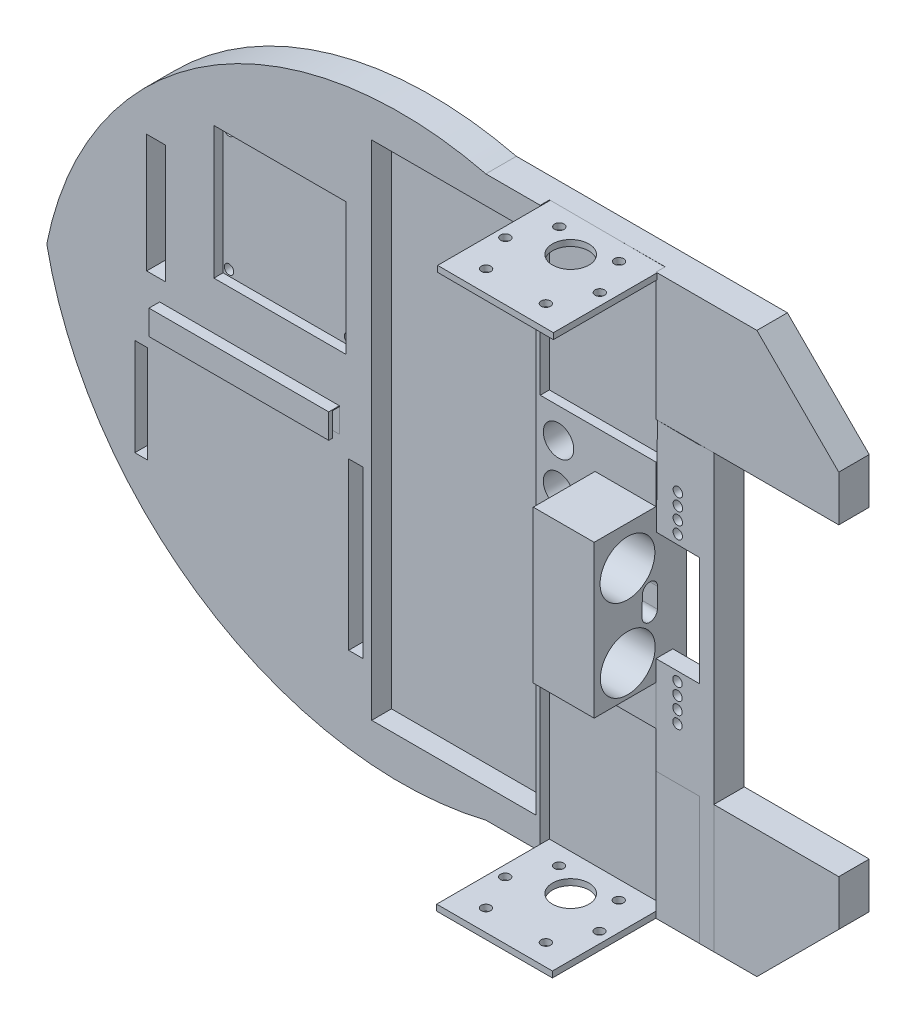
SolidWorks part; units mm, degrees
ref_plane "Front Plane" through (0, 0, 0) normal (0, 0, 1) x (1, 0, 0)
ref_plane "Top Plane" through (0, 0, 0) normal (0, 1, 0) x (1, 0, 0)
ref_plane "Right Plane" through (0, 0, 0) normal (1, 0, 0) x (0, 0, -1)
sketch "Sketch1" plane through (0, 0, 0) normal (0, 0, 1) x (1, 0, 0)
  line L1 (0, 0) -> (0, -50)
  line L2 (0, 50) -> (60, 50)
  line L3 (0, -50) -> (60, -50)
  line L4 (60, 50) -> (60, 65)
  line L5 (60, -50) -> (60, -65)
  line L6 (60, 65) -> (33.1299, 91.8701)
  line L7 (33.1299, 91.8701) -> (-55.8501, 91.8701)
  line L8 (60, -65) -> (33.1299, -91.8701)
  line L9 (33.1299, -91.8701) -> (-55.8501, -91.8701)
  line L10 (-55.8501, 91.8701) -> (-55.8501, 169.9436) construction
  line L11 (-55.8501, 169.9436) -> (-55.8501, -262.005) construction
  line L22 (0, 50) -> (0, 0)
  line L24 (-83.882, 95.237) -> (-230.9548, 95.237) construction
  line L25 (-83.882, 23.2048) -> (-83.882, 138.7176) construction
  line L26 (-83.882, -23.1381) -> (-83.882, -112.3942) construction
  line L27 (-83.882, -95.2351) -> (-171.3154, -95.2351) construction
  arc A7 (-200, -0.1322) -> (-55.8501, 91.8701) centre (-83.882, -23.1381) cw
  arc A8 (-55.8501, -91.8701) -> (-200, -0.1322) centre (-83.882, 23.2048) cw
  dimension "D11" = 199.5908
  dimension "D12" = 200
  dimension "D10" = 183.7401
  dimension "D1" = 50
  dimension "D2" = 50
  dimension "D3" = 60
  dimension "D4" = 15
  dimension "D5" = 15
  dimension "D6" = 135
  dimension "D7" = 38
  dimension "D8" = 38
  dimension "D9" = 135
  dimension "D15" = 88.98
  dimension "D16" = 88.98
extrude "Boss-Extrude1" add sketch "Sketch1" along normal blind 10 and the other way blind 0.01
sketch "Sketch3" plane through (0, 0, 10) normal (0, 0, 1) x (1, 0, 0)
  line L0 (33.1299, 91.8701) -> (-55.8501, 91.8701) construction
  line L1 (-38, 91.8701) -> (0, 91.8701)
  line L2 (-38, 91.8701) -> (-38, 37.8701)
  line L3 (-38, 37.8701) -> (0, 37.8701)
  line L4 (0, 91.8701) -> (0, 37.8701)
  dimension "D1" = 54
extrude "Cut-Extrude1" cut sketch "Sketch3" against normal blind 3 contours L2 L1 L4 L3
sketch "Sketch5" plane through (0, 0, 10) normal (0, 0, 1) x (1, 0, 0)
  line L0 (-55.8501, -91.8701) -> (33.1299, -91.8701) construction
  line L1 (-38, -37.8701) -> (0, -37.8701)
  line L2 (-38, -37.8701) -> (-38, -91.8701)
  line L3 (-38, -91.8701) -> (0, -91.8701)
  line L4 (0, -37.8701) -> (0, -91.8701)
  dimension "D1" = 54
extrude "Cut-Extrude3" cut sketch "Sketch5" against normal blind 3
sketch "Sketch7" plane through (0, 0, 10) normal (0, 0, 1) x (1, 0, 0)
  line L9 (-93.3252, 82.7857) -> (-39.3252, 82.7857)
  line L10 (-93.3252, 82.7857) -> (-93.3252, -82.2143)
  line L11 (-93.3252, -82.2143) -> (-39.3252, -82.2143)
  line L12 (-39.3252, 82.7857) -> (-39.3252, -82.2143)
  dimension "D1" = 54
  dimension "D2" = 165
extrude "Cut-Extrude4" cut sketch "Sketch7" against normal blind 6.5
sketch "Sketch8" plane through (0, 0, 10) normal (0, 0, 1) x (1, 0, 0)
  line L1 (-162.9927, 67.8133) -> (-84.7927, 67.8133)
  line L2 (-162.9927, 67.8133) -> (-162.9927, 10.3133)
  line L3 (-162.9927, 10.3133) -> (-84.7927, 10.3133)
  line L4 (-84.7927, 67.8133) -> (-84.7927, 10.3133)
  dimension "D1" = 78.2
  dimension "D2" = 57.5
extrude "Cut-Extrude5" [suppressed] cut sketch "Sketch8" against normal blind 3
sketch "Sketch9" plane through (0, 0, 10) normal (0, 0, 1) x (1, 0, 0)
  line L1 (-195, 36) -> (-176, 36)
  line L2 (-195, 36) -> (-195, 20)
  line L3 (-195, 20) -> (-176, 20)
  line L4 (-176, 36) -> (-176, 20)
  line L5 (-95.7317, 17.4542) -> (-82.493, 17.4542)
  line L6 (-95.7317, 17.4542) -> (-95.7317, 7.0108)
  line L7 (-95.7317, 7.0108) -> (-82.493, 7.0108)
  line L8 (-82.493, 17.4542) -> (-82.493, 7.0108)
  line L9 (-131.8867, -50.9252) -> (-116.9909, -50.9252)
  line L10 (-131.8867, -50.9252) -> (-131.8867, -65.1638)
  line L11 (-131.8867, -65.1638) -> (-116.9909, -65.1638)
  line L12 (-116.9909, -50.9252) -> (-116.9909, -65.1638)
extrude "Boss-Extrude2" [suppressed] add sketch "Sketch9" along normal blind 20.3
sketch "Sketch15" plane through (0, 0, 10) normal (0, 0, 1) x (1, 0, 0)
  line L0 (0, -37.8701) -> (0, 37.8701) construction
  line L1 (-20, 25.2016) -> (0, 25.2016)
  line L2 (-20, 25.2016) -> (-20, -24.7984)
  line L3 (-20, -24.7984) -> (0, -24.7984)
  line L4 (0, 25.2016) -> (0, -24.7984)
  dimension "D1" = 50
  dimension "D2" = 20
extrude "Boss-Extrude3" add sketch "Sketch15" along normal blind 20.3
sketch "Sketch16" plane through (0, 0, 10) normal (0, 0, 1) x (1, 0, 0)
  line L1 (-232.4208, 4) -> (-224.8235, 4)
  line L2 (-232.4208, 4) -> (-232.4208, -4)
  line L3 (-232.4208, -4) -> (-224.8235, -4)
  line L4 (-224.8235, 4) -> (-224.8235, -4)
  line L9 (-134.6881, 94.0493) -> (-144.6881, 94.0493)
  line L10 (-134.6881, 94.0493) -> (-134.6881, 84.6493)
  line L11 (-134.6881, 84.6493) -> (-144.6881, 84.6493)
  line L12 (-144.6881, 94.0493) -> (-144.6881, 84.6493)
  line L13 (-65.6779, 70.3488) -> (-74.3779, 70.3488)
  line L14 (-65.6779, 70.3488) -> (-65.6779, 61.8488)
  line L15 (-65.6779, 61.8488) -> (-74.3779, 61.8488)
  line L16 (-74.3779, 70.3488) -> (-74.3779, 61.8488)
  line L17 (-65.9779, -61.6233) -> (-75.3779, -61.6233)
  line L18 (-65.9779, -61.6233) -> (-65.9779, -70.9233)
  line L19 (-65.9779, -70.9233) -> (-75.3779, -70.9233)
  line L20 (-75.3779, -61.6233) -> (-75.3779, -70.9233)
  line L21 (-134.6881, -83.6815) -> (-144.6881, -83.6815)
  line L22 (-134.6881, -83.6815) -> (-134.6881, -92.9815)
  line L23 (-134.6881, -92.9815) -> (-144.6881, -92.9815)
  line L24 (-144.6881, -83.6815) -> (-144.6881, -92.9815)
extrude "Boss-Extrude4" [suppressed] add sketch "Sketch16" along normal blind 30
sketch "Sketch17" plane through (0, 0, 0) normal (0, 0, 1) x (1, 0, 0)
  circle A1 centre (-228.4208, 0) radius 2.55
  circle A2 centre (-139.6881, 89.6493) radius 3.5
  circle A3 centre (-69.8779, 66.3488) radius 3.5
  circle A4 centre (-69.8779, -66.6233) radius 3.5
  circle A5 centre (-139.6881, -88.6815) radius 3.5
extrude "Cut-Extrude17" [suppressed] cut sketch "Sketch17" along normal through all
sketch "Sketch18" plane through (0, 0, 10) normal (0, 0, 1) x (1, 0, 0)
  line L1 (-145.1245, 61) -> (-101.7245, 61)
  line L2 (-145.1245, 61) -> (-145.1245, 17.6)
  line L3 (-145.1245, 17.6) -> (-101.7245, 17.6)
  line L4 (-101.7245, 61) -> (-101.7245, 17.6)
  dimension "D1" = 43.4
  dimension "43.4" = 43.4
extrude "Cut-Extrude18" cut sketch "Sketch18" against normal blind 3
sketch "Sketch20" plane through (0, 0, 0) normal (0, 0, 1) x (1, 0, 0)
  circle A0 centre (-185.9471, 27.1121) radius 5
  circle A1 centre (-124.7094, -57.6129) radius 5
  circle A2 centre (-88.8879, 12.7504) radius 4
extrude "Cut-Extrude20" [suppressed] cut sketch "Sketch20" along normal through all
sketch "Sketch21" plane through (0, 0, 0) normal (1, 0, 0) x (0, 0, -1)
  line L0 (-3.8276, 29.0855) -> (-3.8276, -37.1575) construction
  line L1 (-6.4886, 28.3852) -> (-6.4886, -37.2976) construction
  line L2 (-5.0881, 28.1051) -> (-5.0881, -37.5777) construction
  line L3 (-11.99, 2.3019) -> (-12.0559, -4.1532) construction
  line L4 (-9.4916, 2.2764) -> (-9.5574, -4.1787)
  line L5 (-14.4885, 2.3274) -> (-14.5544, -4.1277)
  circle A0 centre (-19.3619, 12.3718) radius 9
  circle A1 centre (-19.2654, -14.6282) radius 9
  arc A2 (-9.4916, 2.2764) -> (-14.4885, 2.3274) centre (-11.99, 2.3019) ccw
  arc A3 (-14.5544, -4.1277) -> (-9.5574, -4.1787) centre (-12.0559, -4.1532) ccw
  point P12 (-12.023, -0.9256)
  dimension "D1" = 18
  dimension "D2" = 18
  dimension "D3" = 27
extrude "Cut-Extrude21" cut sketch "Sketch21" against normal up to surface (20 mm away) up to face at (-20, 0.2016, 20.15)
sketch "Sketch22" plane through (0, 0, 7) normal (0, 0, 1) x (1, 0, 0)
  circle A0 centre (-143.1686, 58.9795) radius 1.55
  circle A1 centre (-103.7686, 58.9795) radius 1.55
  circle A2 centre (-103.7686, 19.5795) radius 1.55
  circle A3 centre (-143.1686, 19.5795) radius 1.55
  dimension "D1" = 2
  dimension "D2" = 2
extrude "Cut-Extrude23" cut sketch "Sketch22" against normal through all
sketch "Sketch25" plane through (0, 0, 10) normal (0, 0, 1) x (1, 0, 0)
  line L5 (-162.9326, 1.9159) -> (-103.9326, 1.9159)
  line L6 (-162.9326, 1.9159) -> (-162.9326, -6.1841)
  line L7 (-162.9326, -6.1841) -> (-103.9326, -6.1841)
  line L8 (-103.9326, 1.9159) -> (-103.9326, -6.1841)
  dimension "D1" = 8.1
  dimension "D2" = 59
extrude "Boss-Extrude5" add sketch "Sketch25" along normal blind 3.5
sketch "Sketch26" plane through (0, -6.1841, 0) normal (0, -1, 0) x (1, 0, 0)
  line L0 (-172.679, 10.0037) -> (-152.674, 9.9893) construction
  line L1 (-152.674, 9.9893) -> (-152.6595, 14.6073) construction
extrude "Cut-Extrude24" [suppressed] cut sketch "Sketch26" against normal up to surface (58.5 mm away)
sketch "Sketch28" plane through (0, -91.8701, 0) normal (0, -1, 0) x (1, 0, 0)
  line L1 (14.2266, 10.0076) -> (18.9795, 10.0076)
  line L2 (14.2266, 10.0076) -> (14.2266, 0.0598)
  line L3 (14.2266, 0.0598) -> (18.9795, 0.0598)
  line L4 (18.9795, 10.0076) -> (18.9795, 0.0598)
extrude "Boss-Extrude6" add sketch "Sketch28" against normal up to surface (141.8701 mm away) up to face at (24, 50, 5.396)
sketch "Sketch34" plane through (0, 0, 10) normal (0, 0, 1) x (1, 0, 0)
  line L0 (0, 0) -> (85.4359, -0.2266) construction
  line L1 (53.8089, -34.3247) -> (61.9289, -40.2214)
  line L2 (53.8089, -34.3247) -> (57.1772, -29.6864)
  line L3 (61.9289, -40.2214) -> (65.2973, -35.5831)
  line L4 (57.1772, -29.6864) -> (65.2973, -35.5831)
  line L5 (62.1414, 39.8924) -> (65.4851, 35.2362)
  line L6 (57.3338, 29.3826) -> (65.4851, 35.2362)
  line L7 (53.9902, 34.0388) -> (57.3338, 29.3826)
  line L8 (53.9902, 34.0388) -> (62.1414, 39.8924)
extrude "Cut-Extrude27" [suppressed] cut sketch "Sketch34" against normal through all
sketch "Sketch36" plane through (0, 0, 7) normal (0, 0, 1) x (1, 0, 0)
  line L0 (0, 0) -> (106.9048, -0.1896) construction
  line L1 (0.3256, 91.8145) -> (0.3185, 89.8146)
  line L2 (0, -91.8151) -> (-38, -91.8151)
  line L3 (0, -91.8151) -> (0, -89.8151)
  line L4 (0, -89.8151) -> (-38, -89.8151)
  line L5 (-38, -91.8151) -> (-38, -89.8151)
  line L6 (-37.6741, 91.9493) -> (-37.6812, 89.9493)
  line L7 (0.3185, 89.8146) -> (-37.6812, 89.9493)
  line L8 (0.3256, 91.8145) -> (-37.6741, 91.9493)
  dimension "D1" = 2
extrude "Boss-Extrude7" add sketch "Sketch36" along normal blind 37
sketch "Sketch39" plane through (0, -91.8151, 0) normal (0, -1, 0) x (1, 0, 0)
  line L1 (-46.4365, 25) -> (22.9075, 25) construction
  line L4 (31.9978, 332) -> (-461.8231, 332) construction
  circle A1 centre (-19, 19) radius 6
  circle A2 centre (-34.4996, 25.0106) radius 1.55
  circle A3 centre (-3.5639, 24.9888) radius 1.55
  circle A4 centre (-28.8192, 37.0106) radius 1.55
  circle A5 centre (-9.1774, 36.9888) radius 1.55
  circle A6 centre (-28.82, 13.0106) radius 1.55
  circle A7 centre (-9.2305, 12.9888) radius 1.55
  point P18 (6.9989, 178.85)
  dimension "D1" = 12
  dimension "D5" = 12
  dimension "D6" = 12
  dimension "D7" = 12
  dimension "D8" = 12
  dimension "D2" = 19
extrude "Cut-Extrude28" cut sketch "Sketch39" against normal up to surface (2 mm away) up to face at (-19, -89.8151, 20.3333)
sketch "Sketch42" plane through (0.3256, 91.8145, 0) normal (0.0035, 1, 0) x (1, -0.0035, 0)
  circle A7 centre (-19.3258, -19) radius 6
  circle A9 centre (-29.0701, -13) radius 1.55
  circle A10 centre (-3.7784, -25) radius 1.55
  circle A11 centre (-9.4641, -13) radius 1.55
  circle A12 centre (-34.7723, -25) radius 1.55
  circle A13 centre (-29.0965, -37) radius 1.55
  circle A14 centre (-9.4734, -37) radius 1.55
  dimension "D1" = 12
  dimension "D5" = 6
  dimension "D6" = 6
  dimension "D7" = 6
  dimension "D8" = 6
  dimension "D9" = 18
  dimension "D10" = 18
  dimension "D2" = 19
extrude "Cut-Extrude29" cut sketch "Sketch42" against normal up to surface (2 mm away) up to face at (-12.4542, 89.8599, 20.3333)
sketch "Sketch44" plane through (-162.9326, 0, 0) normal (-1, 0, 0) x (0, 0, 1)
  line L1 (12.2622, 1.6288) -> (10.0122, 1.6288)
  line L2 (12.2622, 1.6288) -> (12.2622, -6.1912)
  line L3 (12.2622, -6.1912) -> (10.0122, -6.1912)
  line L4 (10.0122, 1.6288) -> (10.0122, -6.1912)
  dimension "D1" = 2.25
  dimension "D2" = 7.82
extrude "Cut-Extrude30" cut sketch "Sketch44" against normal up to surface (59 mm away) up to face at (-103.9326, -2.1341, 11.75)
sketch "Sketch45" plane through (0, 0, -0.01) normal (0, 0, -1) x (-1, 0, 0)
  line L0 (0, 0) -> (-86.1371, -0.4083) construction
  line L13 (-0.1707, 17.9992) -> (-0.474, 49.9978)
  line L14 (-16.5, -18) -> (0, -18)
  line L15 (-16.5, -18) -> (-16.5, -50)
  line L16 (-16.5, -50) -> (0, -50)
  line L17 (0, -18) -> (0, -50)
  line L18 (-16.9733, 49.8413) -> (-0.474, 49.9978)
  line L19 (-16.6699, 17.8428) -> (-16.9733, 49.8413)
  line L20 (-16.6699, 17.8428) -> (-0.1707, 17.9992)
extrude "Boss-Extrude8" add sketch "Sketch45" against normal up to surface (10.0176 mm away) up to face at (16.6031, -20.935, 10.0076)
sketch "Sketch30" plane through (0, 0, -0.01) normal (0, 0, -1) x (-1, 0, 0)
  line L0 (0.5881, -0.0011) -> (-26.6848, -0.0585) construction
  line L1 (0, -41.01) -> (-14.12, -41.01)
  line L2 (0, -41.01) -> (0, -16.01)
  line L3 (0, -16.01) -> (-14.12, -16.01)
  line L4 (-14.12, -41.01) -> (-14.12, -16.01)
  line L5 (-14.2924, 40.9456) -> (-14.1872, 15.9458)
  line L6 (-0.0674, 16.0052) -> (-14.1872, 15.9458)
  line L7 (-0.1725, 41.005) -> (-0.0674, 16.0052)
  line L8 (-0.1725, 41.005) -> (-14.2924, 40.9456)
  dimension "D1" = 25
  dimension "D2" = 14.12
extrude "Cut-Extrude25" cut sketch "Sketch30" against normal blind 4.5
sketch "Sketch33" plane through (0, 0, -0.01) normal (0, 0, -1) x (-1, 0, 0)
  line L0 (0, 0) -> (-115.8951, -0.2361) construction
  circle A0 centre (-7.06, -33) radius 1.55
  circle A1 centre (-7.06, -29) radius 1.55
  circle A2 centre (-7.06, -25) radius 1.55
  circle A3 centre (-7.06, -21) radius 1.55
  circle A4 centre (-7.1455, 20.9711) radius 1.55
  circle A5 centre (-7.1618, 24.971) radius 1.55
  circle A6 centre (-7.1781, 28.971) radius 1.55
  circle A7 centre (-7.1944, 32.971) radius 1.55
  dimension "D1" = 4
extrude "Cut-Extrude26" cut sketch "Sketch33" against normal up to surface (10.0176 mm away) up to face at (9.5356, -8.3699, 10.0076)
sketch "Sketch46" plane through (0, 0, 10) normal (0, 0, 1) x (1, 0, 0)
  circle A0 centre (-32, 28) radius 5
  circle A1 centre (-32, 14) radius 5
  circle A2 centre (-32, 0) radius 5
  circle A3 centre (-32, -14) radius 5
  circle A4 centre (-32, -28) radius 5
  dimension "D1" = 5
extrude "Cut-Extrude31" cut sketch "Sketch46" against normal through all
sketch "Sketch47" plane through (0, 0, 10) normal (0, 0, 1) x (1, 0, 0)
  line L1 (-167.202, 47.4765) -> (-161.0629, 47.4765)
  line L2 (-167.202, 47.4765) -> (-167.202, 8.5957)
  line L3 (-167.202, 8.5957) -> (-161.0629, 8.5957)
  line L4 (-161.0629, 47.4765) -> (-161.0629, 8.5957)
  line L5 (-100.9, -11.6633) -> (-96.1934, -11.6633)
  line L6 (-100.9, -11.6633) -> (-100.9, -66.0964)
  line L7 (-100.9, -66.0964) -> (-96.1934, -66.0964)
  line L8 (-96.1934, -11.6633) -> (-96.1934, -66.0964)
  line L9 (-171.0901, -13.0957) -> (-166.9973, -13.0957)
  line L10 (-171.0901, -13.0957) -> (-171.0901, -45.0189)
  line L11 (-171.0901, -45.0189) -> (-166.9973, -45.0189)
  line L12 (-166.9973, -13.0957) -> (-166.9973, -45.0189)
extrude "Cut-Extrude32" cut sketch "Sketch47" against normal through all
